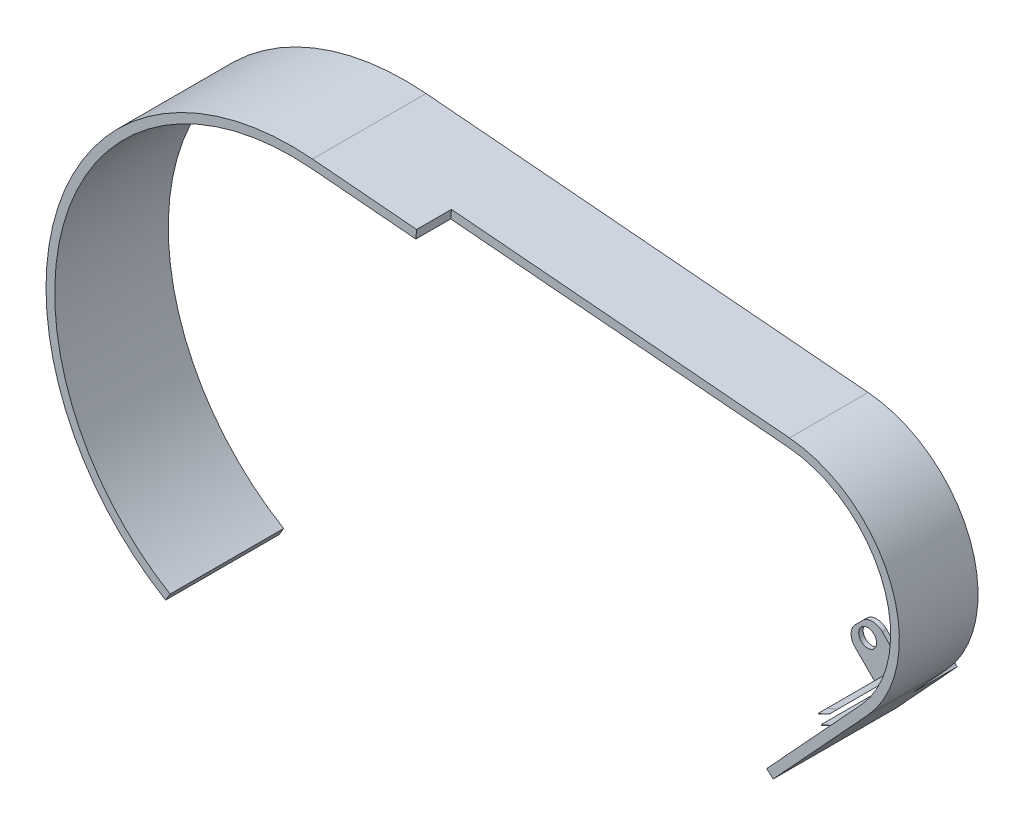
SolidWorks part; units mm, degrees
ref_plane "Front Plane" through (0, 0, 0) normal (0, 0, 1) x (1, 0, 0)
ref_plane "Top Plane" through (0, 0, 0) normal (0, 1, 0) x (1, 0, 0)
ref_plane "Right Plane" through (0, 0, 0) normal (1, 0, 0) x (0, 0, -1)
sketch "Sketch1" plane through (0, 0, 0) normal (0, 0, 1) x (1, 0, 0)
  line L0 (121.6679, 181.2951) -> (282.8673, 167.4918)
  line L1 (153.0564, 18.0749) -> (297.6383, 90.6823)
  line L2 (283.1381, 170.6552) -> (121.9388, 184.4585)
  line L3 (154.4813, 15.2376) -> (298.1618, 87.3924)
  line L4 (36.5877, 50.783) -> (13.6453, 23.6139)
  line L5 (53.8588, 29.1942) -> (22.3162, 12.7753)
  line L6 (68.3731, 18.3914) -> (160.7614, 18.3914) construction
  line L7 (114.3, 95.25) -> (68.3731, 18.3914)
  line L8 (294.8392, 85.7238) -> (264.7021, 85.7238) construction
  line L9 (279.4, 127) -> (294.8392, 85.7238)
  line L10 (309.2815, 99.4554) -> (274.8507, 62.1035)
  line L11 (274.8507, 62.1035) -> (277.1852, 59.9516)
  line L12 (277.1852, 59.9516) -> (311.616, 97.3034)
  circle A1 centre (19.05, 19.05) radius 3.2639 construction
  circle A2 centre (19.05, 19.05) radius 3.2639
  circle A3 centre (19.05, 19.05) radius 7.0739
  arc A4 (25.1637, 15.4915) -> (15.2029, 24.9863) centre (19.05, 19.05) ccw construction
  arc A5 (25.1637, 15.4915) -> (15.2029, 24.9863) centre (19.05, 19.05) ccw
  circle A6 centre (279.4, 127) radius 20.2311 construction
  circle A7 centre (279.4, 127) radius 20.2311
  circle A8 centre (279.4, 127) radius 40.64
  circle A9 centre (114.3, 95.25) radius 35.7643 construction
  circle A10 centre (114.3, 95.25) radius 35.7643
  circle A11 centre (114.3, 95.25) radius 86.36
  circle A12 centre (114.3, 95.25) radius 89.535
  arc A13 (311.616, 97.3034) -> (298.1829, 87.4152) centre (279.4, 127) ccw
  arc A14 (117.9296, 28.7195) -> (118.5852, 20.7913) centre (113.7881, 24.3858) ccw construction
  arc A15 (117.9296, 28.7195) -> (118.5852, 20.7913) centre (113.7881, 24.3858) ccw construction
  arc A16 (261.4121, 86.1246) -> (257.9665, 92.9191) centre (263.5195, 91.4642) ccw construction
  arc A17 (261.4121, 86.1246) -> (257.9665, 92.9191) centre (263.5195, 91.4642) ccw construction
  dimension "D1" = 81.28
  dimension "D2" = 172.72
  dimension "D3" = 3.175
  dimension "D4" = 3.175
  dimension "D5" = 35.56
  dimension "D6" = 35.56
  dimension "D7" = 50.8
extrude "Boss-Extrude1" add sketch "Sketch1" along normal blind 25.4 contours A13 L0 A8 L1 L9 | A8 L9 L1 | A13 L9 L3 | A13 L2 A12 L0 | L0 A12 L7 A11
sketch "Sketch2" plane through (0, 0, 0) normal (0, 0, -1) x (-1, 0, 0)
  line L0 (-114.3, 95.25) -> (-68.3731, 18.3914) construction
  line L1 (-121.6679, 181.2951) -> (-282.8673, 167.4918) construction
  line L2 (-53.8588, 29.1942) -> (-22.3162, 12.7753) construction
  line L3 (-36.5877, 50.783) -> (-13.6453, 23.6139) construction
  line L4 (-154.4813, 15.2376) -> (-298.1618, 87.3924) construction
  line L5 (-283.1381, 170.6552) -> (-121.9388, 184.4585) construction
  line L6 (-153.0564, 18.0749) -> (-297.6383, 90.6823) construction
  line L7 (-279.4, 127) -> (-294.8392, 85.7238) construction
  line L8 (-114.3, 95.25) -> (-68.3731, 18.3914)
  line L9 (-121.6679, 181.2951) -> (-282.8673, 167.4918)
  line L10 (-53.8588, 29.1942) -> (-22.3162, 12.7753)
  line L11 (-36.5877, 50.783) -> (-13.6453, 23.6139)
  line L12 (-154.4813, 15.2376) -> (-298.1618, 87.3924)
  line L13 (-283.1381, 170.6552) -> (-121.9388, 184.4585)
  line L14 (-153.0564, 18.0749) -> (-297.6383, 90.6823)
  line L15 (-279.4, 127) -> (-294.8392, 85.7238)
  arc A0 (-15.2029, 24.9863) -> (-25.1637, 15.4915) centre (-19.05, 19.05) ccw construction
  circle A1 centre (-114.3, 95.25) radius 86.36
  circle A2 centre (-114.3, 95.25) radius 86.36
  circle A3 centre (-114.3, 95.25) radius 35.7643
  circle A4 centre (-114.3, 95.25) radius 35.7643
  circle A5 centre (-279.4, 127) radius 40.64
  circle A6 centre (-279.4, 127) radius 40.64
  circle A7 centre (-279.4, 127) radius 20.2311
  circle A8 centre (-279.4, 127) radius 20.2311
  circle A9 centre (-19.05, 19.05) radius 7.0739
  circle A10 centre (-19.05, 19.05) radius 7.0739
  circle A11 centre (-19.05, 19.05) radius 3.2639
  circle A12 centre (-19.05, 19.05) radius 3.2639
  circle A14 centre (-279.4, 127) radius 43.815
  circle A15 centre (-114.3, 95.25) radius 89.535
  circle A16 centre (-114.3, 95.25) radius 89.535
  arc A17 (-15.2029, 24.9863) -> (-25.1637, 15.4915) centre (-19.05, 19.05) ccw
  arc M16 (-68.3731, 18.3914) -> (-121.9388, 184.4585) centre (-114.3, 95.25) ccw
  dimension "D7" = 87.63
  dimension "D1" = 0
  dimension "D2" = 0
  dimension "D3" = 0
  dimension "D4" = 0
  dimension "D5" = 0
  dimension "D6" = 0
  dimension "D8" = 0
extrude "Boss-Extrude2" add sketch "Sketch2" against normal blind 3.175 contours A10 L11 L10 M16 | A10 A12
sketch "Sketch3" plane through (0, 0, 25.4) normal (0, 0, 1) x (1, 0, 0)
  line L0 (114.3, 95.25) -> (68.3731, 18.3914) construction
  line L1 (121.6679, 181.2951) -> (282.8673, 167.4918) construction
  line L2 (53.8588, 29.1942) -> (22.3162, 12.7753) construction
  line L3 (36.5877, 50.783) -> (13.6453, 23.6139) construction
  line L4 (154.4813, 15.2376) -> (298.1618, 87.3924) construction
  line L5 (283.1381, 170.6552) -> (121.9388, 184.4585) construction
  line L6 (153.0564, 18.0749) -> (297.6383, 90.6823) construction
  line L7 (279.4, 127) -> (294.8392, 85.7238) construction
  line L8 (114.3, 95.25) -> (68.3731, 18.3914)
  line L9 (121.6679, 181.2951) -> (282.8673, 167.4918)
  line L10 (53.8588, 29.1942) -> (22.3162, 12.7753)
  line L11 (36.5877, 50.783) -> (13.6453, 23.6139)
  line L12 (154.4813, 15.2376) -> (298.1618, 87.3924)
  line L13 (283.1381, 170.6552) -> (121.9388, 184.4585)
  line L14 (153.0564, 18.0749) -> (297.6383, 90.6823)
  line L15 (279.4, 127) -> (294.8392, 85.7238)
  arc A0 (25.1637, 15.4915) -> (15.2029, 24.9863) centre (19.05, 19.05) ccw construction
  circle A1 centre (114.3, 95.25) radius 86.36
  circle A2 centre (114.3, 95.25) radius 86.36
  circle A3 centre (114.3, 95.25) radius 35.7643
  circle A4 centre (114.3, 95.25) radius 35.7643
  circle A5 centre (279.4, 127) radius 40.64
  circle A6 centre (279.4, 127) radius 40.64
  circle A7 centre (279.4, 127) radius 20.2311
  circle A8 centre (279.4, 127) radius 20.2311
  circle A9 centre (19.05, 19.05) radius 7.0739
  circle A10 centre (19.05, 19.05) radius 7.0739
  circle A11 centre (19.05, 19.05) radius 3.2639
  circle A12 centre (19.05, 19.05) radius 3.2639
  circle A14 centre (279.4, 127) radius 43.815
  circle A15 centre (114.3, 95.25) radius 89.535
  circle A16 centre (114.3, 95.25) radius 89.535
  arc A17 (25.1637, 15.4915) -> (15.2029, 24.9863) centre (19.05, 19.05) ccw
  arc M9 (311.616, 97.3034) -> (283.1381, 170.6552) centre (279.4, 127) ccw
  line M10 (283.1381, 170.6552) -> (121.9388, 184.4585)
  arc M11 (121.9388, 184.4585) -> (68.3731, 18.3914) centre (114.3, 95.25) ccw
  line M12 (68.3731, 18.3914) -> (70.0017, 21.1169)
  arc M13 (70.0017, 21.1169) -> (121.6679, 181.2951) centre (114.3, 95.25) cw
  line M14 (121.6679, 181.2951) -> (282.8673, 167.4918)
  arc M15 (282.8673, 167.4918) -> (309.2815, 99.4554) centre (279.4, 127) cw
  line M16 (294.7502, 85.9619) -> (294.8392, 85.7238)
  line M17 (294.8392, 85.7238) -> (298.1618, 87.3924)
  dimension "D7" = 87.63
  dimension "D1" = 0
  dimension "D2" = 0
  dimension "D3" = 0
  dimension "D4" = 0
  dimension "D5" = 0
  dimension "D6" = 0
  dimension "D8" = 0
extrude "Boss-Extrude3" add sketch "Sketch3" along normal blind 3.302 contours A16 M14 M11 M12 M13 | A16 L9 A14 M10 | A14 L9 L14 M9 M15 M16 | L14 M16 M15 | A14 L15 M17 | A2
sketch "Sketch4" plane through (0, 0, 28.702) normal (0, 0, 1) x (1, 0, 0)
  line L0 (121.6679, 181.2951) -> (282.8673, 167.4918) construction
  line L1 (283.1381, 170.6552) -> (121.9388, 184.4585) construction
  line L2 (121.6679, 181.2951) -> (159.629, 178.0446)
  line L3 (159.8999, 181.208) -> (121.9388, 184.4585)
  line L4 (159.8999, 181.208) -> (159.629, 178.0446)
  line L5 (121.9388, 184.4585) -> (121.6679, 181.2951) construction
  line L6 (68.3731, 18.3914) -> (70.0017, 21.1169) construction
  line L7 (68.3731, 18.3914) -> (70.0017, 21.1169)
  arc A0 (121.6679, 181.2951) -> (70.0017, 21.1169) centre (114.3, 95.25) ccw construction
  arc A1 (121.9388, 184.4585) -> (68.3731, 18.3914) centre (114.3, 95.25) ccw construction
  arc A2 (121.6679, 181.2951) -> (70.0017, 21.1169) centre (114.3, 95.25) ccw
  arc A3 (121.9388, 184.4585) -> (68.3731, 18.3914) centre (114.3, 95.25) ccw
  dimension "D1" = 38.1
extrude "Boss-Extrude4" add sketch "Sketch4" along normal blind 12.7
sketch "Sketch5" plane through (0, 0, 0) normal (0, 0, -1) x (-1, 0, 0)
  line L0 (-277.1852, 59.9516) -> (-274.8507, 62.1035)
  line L1 (-274.8507, 62.1035) -> (-297.0701, 86.208)
  line L2 (-297.0701, 86.208) -> (-299.4046, 84.0561)
  line L3 (-277.1852, 59.9516) -> (-311.616, 97.3034) construction
  line L4 (-299.4046, 84.0561) -> (-277.1852, 59.9516)
extrude "Boss-Extrude5" add sketch "Sketch5" along normal blind 16.1925
sketch "Sketch6" plane through (0, 0, -16.1925) normal (0, 0, -1) x (-1, 0, 0)
  line L0 (-274.8507, 62.1035) -> (-263.8012, 73.153)
  line L1 (-263.8012, 80.3372) -> (-266.4953, 83.0312)
  line L2 (-273.6795, 83.0312) -> (-284.327, 72.3838)
  line L3 (-274.8507, 62.1035) -> (-297.0701, 86.208) construction
  line L4 (-284.327, 72.3838) -> (-274.8507, 62.1035)
  line L5 (-265.1483, 81.6842) -> (-279.5888, 67.2436) construction
  line L6 (-272.3685, 74.4639) -> (-267.4294, 69.5248) construction
  line L7 (-272.3685, 74.4639) -> (-277.3077, 79.4031) construction
  circle A0 centre (-268.3542, 78.4783) radius 3.2639
  arc A1 (-266.4953, 83.0312) -> (-273.6795, 83.0312) centre (-270.0874, 79.4391) ccw
  arc A2 (-263.8012, 73.153) -> (-263.8012, 80.3372) centre (-267.3933, 76.7451) ccw
  dimension "D2" = 6.5278
  dimension "D3" = 4.5339
  dimension "D5" = 5.08
  dimension "D1" = 13.97
  dimension "D4" = 15.875
extrude "Boss-Extrude6" add sketch "Sketch6" against normal blind 1.5875
